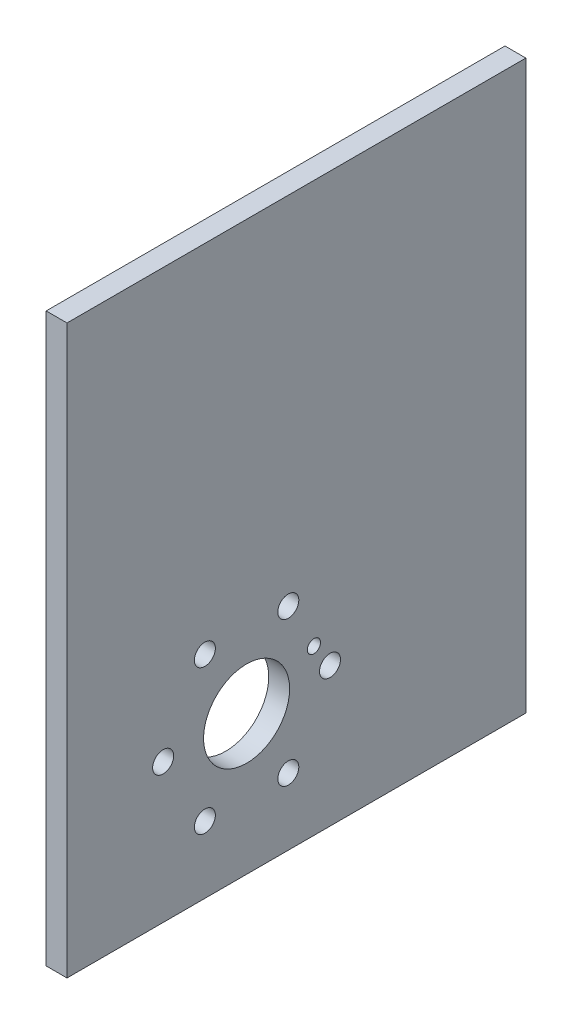
SolidWorks part; units mm, degrees
ref_plane "Front Plane" through (0, 0, 0) normal (0, 0, 1) x (1, 0, 0)
ref_plane "Top Plane" through (0, 0, 0) normal (0, 1, 0) x (1, 0, 0)
ref_plane "Right Plane" through (0, 0, 0) normal (1, 0, 0) x (0, 0, -1)
sketch "Sketch1" plane through (0, 0, 0) normal (1, 0, 0) x (0, 0, -1)
  line L1 (0, 0) -> (69.85, 0)
  line L2 (0, 0) -> (0, 86.36)
  line L3 (0, 86.36) -> (69.85, 86.36)
  line L4 (69.85, 0) -> (69.85, 86.36)
  dimension "D1" = 86.36
  dimension "D2" = 69.85
extrude "Boss-Extrude1" add sketch "Sketch1" along normal blind 3.175
hole_wizard "1/2 Clearance Hole1" positions "Sketch3" profile "Sketch2" hole size "1/2" standard "ANSI Inch"
sketch "Sketch3" plane through (3.175, 0, 0) normal (1, 0, 0) x (0, 0, -1)
  line L0 (0, 0) -> (69.85, 0) construction
  line L1 (0, 86.36) -> (0, 0) construction
  point P0 (27.3378, 21.1869)
  point P3 (34.925, 0)
  dimension "D1" = 21.1869
  dimension "D2" = 27.3378
sketch "Sketch2" plane through (3.175, 21.1869, -27.3378) normal (0, 1, 0) x (0, 0, -1)
  line L0 (0, 0) -> (0, 29.3345)
  line L1 (0, 29.3345) -> (6.5481, 25.4)
  line L2 (6.5481, 25.4) -> (6.5481, 0)
  line L5 (6.5481, 0) -> (0, 0)
  line L10 (0, 29.3345) -> (-6.5481, 25.4) construction
  line L11 (0, -6.35) -> (0, 107.95) construction
  dimension "Hole Dia." = 13.0962
  dimension "Hole Depth" = 25.4
  dimension "Drill Angle" = 118
hole_wizard "M3 Clearance Hole1" positions "Sketch5" profile "Sketch4" hole size "M3" standard "ANSI Metric"
sketch "Sketch5" plane through (0, 0, 0) normal (-1, 0, 0) x (0, 0, 1)
  line L11 (-27.3378, 21.1869) -> (-40.0378, 21.1869) construction
  line L12 (-27.3378, 21.1869) -> (-33.6878, 32.1855) construction
  line L13 (-27.3378, 21.1869) -> (-20.9878, 32.1855) construction
  line L14 (-27.3378, 21.1869) -> (-14.6378, 21.1869) construction
  line L15 (-27.3378, 21.1869) -> (-20.9878, 10.1884) construction
  line L16 (-27.3378, 21.1869) -> (-33.6878, 10.1884) construction
  point P55 (-40.0378, 21.1869)
  point P66 (-33.6878, 32.1855)
  point P67 (-20.9878, 32.1855)
  point P68 (-14.6378, 21.1869)
  point P69 (-20.9878, 10.1884)
  point P70 (-33.6878, 10.1884)
  point P71 (-27.3378, 21.1869)
  dimension "D1" = 12.7
  dimension "D2" = 6
sketch "Sketch4" plane through (0, 21.1869, -40.0378) normal (0, 1, 0) x (0, 0, 1)
  line L0 (0, 0) -> (0, 26.3614)
  line L1 (0, 26.3614) -> (1.6, 25.4)
  line L2 (1.6, 25.4) -> (1.6, 0)
  line L5 (1.6, 0) -> (0, 0)
  line L10 (0, 26.3614) -> (-1.6, 25.4) construction
  line L11 (0, -6.35) -> (0, 107.95) construction
  dimension "Hole Dia." = 3.2
  dimension "Hole Depth" = 25.4
  dimension "Drill Angle" = 118
hole_wizard "Ø2.0mm Clearance Dowel Hole1" positions "Sketch7" profile "Sketch6" hole size "Ø2.0" standard "ANSI Metric"
sketch "Sketch7" plane through (3.175, 0, 0) normal (1, 0, 0) x (0, 0, -1)
  line L0 (0, 86.36) -> (0, 0) construction
  line L1 (0, 0) -> (69.85, 0) construction
  point P0 (37.5906, 24.9513)
  dimension "D1" = 37.5906
  dimension "D2" = 24.9513
sketch "Sketch6" plane through (3.175, 24.9513, -37.5906) normal (0, 1, 0) x (0, 0, -1)
  line L0 (0, 0) -> (0, 26.0009)
  line L1 (0, 26.0009) -> (1, 25.4)
  line L2 (1, 25.4) -> (1, 0)
  line L5 (1, 0) -> (0, 0)
  line L10 (0, 26.0009) -> (-1, 25.4) construction
  line L11 (0, -6.35) -> (0, 107.95) construction
  dimension "Hole Dia." = 2
  dimension "Hole Depth" = 25.4
  dimension "Drill Angle" = 118
